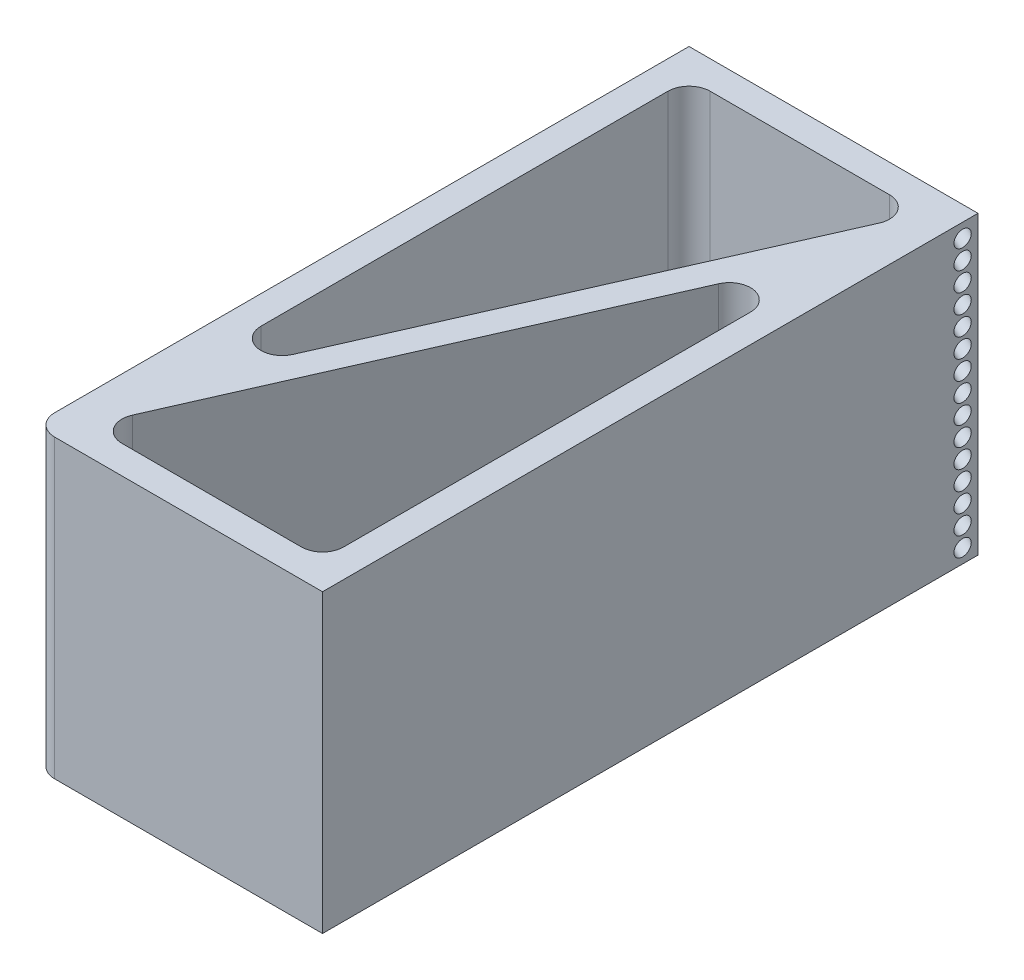
SolidWorks part; units mm, degrees
ref_plane "Front Plane" through (0, 0, 0) normal (0, 0, 1) x (1, 0, 0)
ref_plane "Top Plane" through (0, 0, 0) normal (0, 1, 0) x (1, 0, 0)
ref_plane "Right Plane" through (0, 0, 0) normal (1, 0, 0) x (0, 0, -1)
sketch "Sketch1" plane through (0, 0, 0) normal (0, 1, 0) x (1, 0, 0)
  line L1 (-20.5, -46.5) -> (20.5, -46.5)
  line L2 (-20.5, -46.5) -> (-20.5, 46.5)
  line L3 (-20.5, 46.5) -> (20.5, 46.5)
  line L4 (20.5, -46.5) -> (20.5, 46.5)
  line L5 (-20.5, -46.5) -> (20.5, 46.5) construction
  line L6 (-20.5, 46.5) -> (20.5, -46.5) construction
  point P0 (0, 0)
  dimension "D1" = 41
  dimension "D2" = 93
extrude "Boss-Extrude1" add sketch "Sketch1" along normal blind 42
ref_plane "Plane1" through (0, 0, 0) normal (-0.915, 0, -0.4034) x (-0.4034, 0, 0.915)
sketch "Sketch2" plane through (0, 0, 0) normal (-0.915, 0, -0.4034) x (-0.4034, 0, 0.915)
  line L0 (-50.8183, 42) -> (-50.8183, 0) construction
  line L1 (-50.8183, 42) -> (-50.8183, 0) construction
  line L2 (-48.8183, 42) -> (-48.8183, 0) construction
  line L3 (-50.8183, 42) -> (-34.279, 42) construction
  line L4 (-50.8183, 0) -> (-34.279, 0) construction
  circle A0 centre (-48.8183, 40) radius 1.125
  circle A1 centre (-48.8183, 37.2857) radius 1.125
  circle A2 centre (-48.8183, 34.5714) radius 1.125
  circle A3 centre (-48.8183, 31.8571) radius 1.125
  circle A4 centre (-48.8183, 29.1429) radius 1.125
  circle A5 centre (-48.8183, 26.4286) radius 1.125
  circle A6 centre (-48.8183, 23.7143) radius 1.125
  circle A7 centre (-48.8183, 21) radius 1.125
  circle A8 centre (-48.8183, 18.2857) radius 1.125
  circle A9 centre (-48.8183, 15.5714) radius 1.125
  circle A10 centre (-48.8183, 12.8571) radius 1.125
  circle A11 centre (-48.8183, 10.1429) radius 1.125
  circle A12 centre (-48.8183, 7.4286) radius 1.125
  circle A13 centre (-48.8183, 4.7143) radius 1.125
  circle A14 centre (-48.8183, 2) radius 1.125
  dimension "D2" = 2
  dimension "D5" = 2.25
  dimension "D3" = 2
  dimension "D4" = 2
  dimension "D1" = 15
extrude "Cut-Extrude1" cut sketch "Sketch2" against normal through all both and the other way through all
sketch "Sketch3" plane through (0, 0, 0) normal (0, -1, 0) x (1, 0, 0)
  line L0 (16.5, 42.5) -> (-16.5508, 42.5)
  line L1 (-16.5508, 42.5) -> (16.5, -32.4689)
  line L2 (16.5, -32.4689) -> (16.5, 42.5)
  line L3 (-16.5, 32.4689) -> (16.5508, -42.5)
  line L4 (16.5508, -42.5) -> (-16.5, -42.5)
  line L5 (-16.5, -42.5) -> (-16.5, 32.4689)
  line L6 (-20.5, 46.5) -> (20.5, -46.5) construction
  line L7 (-20.5, 46.5) -> (20.5, 46.5) construction
  line L8 (20.5, 46.5) -> (20.5, -46.5) construction
  line L9 (20.5, -46.5) -> (-20.5, -46.5) construction
  line L10 (-20.5, -46.5) -> (-20.5, 46.5) construction
  point P18 (-14.5491, 26.6601)
  dimension "D1" = 4
  dimension "D2" = 4
  dimension "D3" = 4
  dimension "D4" = 4
  dimension "D5" = 4
extrude "Cut-Extrude2" cut sketch "Sketch3" against normal through all
fillet "Fillet1" radius 3 6 edges at (-16.5, 21, -42.5) (-16.5, 21, 32.4689) (-16.5508, 21, 42.5) (16.5, 21, 42.5) (16.5, 21, -32.4689) (16.5508, 21, -42.5)
fillet "Fillet2" radius 3 1 edges at (-20.5, 21, 46.5)
